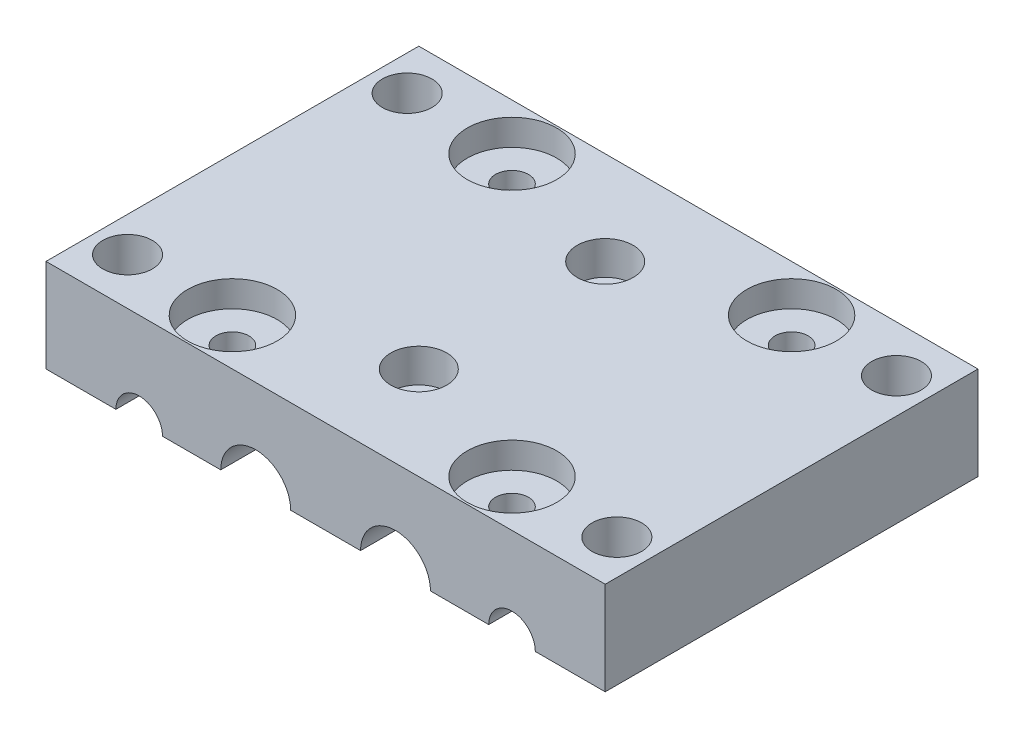
SolidWorks part; units mm, degrees
material "Copper"
ref_plane "Front Plane" through (0, 0, 0) normal (0, 0, 1) x (1, 0, 0)
ref_plane "Top Plane" through (0, 0, 0) normal (0, 1, 0) x (1, 0, 0)
ref_plane "Right Plane" through (0, 0, 0) normal (1, 0, 0) x (0, 0, -1)
sketch "Sketch1" plane through (0, 0, 0) normal (0, 1, 0) x (1, 0, 0)
  line L1 (-38.1, 25.4) -> (38.1, 25.4)
  line L2 (-38.1, 25.4) -> (-38.1, -25.4)
  line L3 (-38.1, -25.4) -> (38.1, -25.4)
  line L4 (38.1, 25.4) -> (38.1, -25.4)
  dimension "D1" = 50.8
  dimension "D2" = 76.2
  dimension "D3" = 38.1
  dimension "D4" = 25.4
extrude "Boss-Extrude1" add sketch "Sketch1" along normal blind 12.7
sketch "Sketch2" plane through (0, 0, 25.4) normal (0, 0, 1) x (1, 0, 0)
  line L0 (-38.1, 0) -> (38.1, 0) construction
  line L1 (-38.1, 12.7) -> (-38.1, 0) construction
  circle A0 centre (-25.4, 0) radius 3.175
  circle A1 centre (25.4, 0) radius 3.175
  dimension "D3" = 6.35
  dimension "D1" = 50.8
  dimension "D2" = 12.7
extrude "Cut-Extrude1" cut sketch "Sketch2" against normal through all
sketch "Sketch3" plane through (0, 0, 25.4) normal (0, 0, 1) x (1, 0, 0)
  line L0 (-22.225, 0) -> (22.225, 0) construction
  circle A0 centre (-9.525, 0) radius 4.7625
  circle A1 centre (9.525, 0) radius 4.7625
  dimension "D1" = 9.525
  dimension "D2" = 19.05
  dimension "D3" = 9.525
extrude "Cut-Extrude2" cut sketch "Sketch3" against normal through all
hole_wizard "1/4 Clearance Hole1" positions "Sketch5" profile "Sketch4" hole size "1/4" standard "ANSI Inch" end condition through all
sketch "Sketch5" plane through (0, 12.7, 0) normal (0, 1, 0) x (1, 0, 0)
  line L0 (-38.1, 25.4) -> (-38.1, -25.4) construction
  line L1 (38.1, 25.4) -> (-38.1, 25.4) construction
  line L2 (-38.1, -25.4) -> (-28.575, -25.4) construction
  line L3 (38.1, -25.4) -> (38.1, 25.4) construction
  point P0 (-33.3375, -19.05)
  point P2 (-33.3375, 19.05)
  point P4 (33.3375, 19.05)
  point P6 (33.3375, -19.05)
  point P17 (-33.3375, -25.4)
  dimension "D1" = 4.7625
  dimension "D2" = 6.35
  dimension "D3" = 6.35
  dimension "D4" = 4.7625
sketch "Sketch4" plane through (-33.3375, 12.7, 19.05) normal (1, 0, 0) x (0, 0, 1)
  line L0 (0, 0) -> (0, 12.7)
  line L1 (0, 12.7) -> (3.3782, 12.7)
  line L2 (3.3782, 12.7) -> (3.3782, 0)
  line L5 (3.3782, 0) -> (0, 0)
  line L11 (0, -6.35) -> (0, 107.95) construction
  dimension "Thru Hole Dia." = 6.7564
  dimension "Thru Hole Depth" = 12.7
hole_wizard "#8 Clearance Hole1" positions "Sketch7" profile "Sketch6" hole size "#8" standard "ANSI Inch" end condition through all
sketch "Sketch7" plane through (0, 12.7, 0) normal (0, 1, 0) x (1, 0, 0)
  point P0 (-19.05, 19.05)
  point P2 (-19.05, -19.05)
  point P4 (19.05, -19.05)
  point P6 (19.05, 19.05)
  point P14 (0, 12.7)
  point P16 (0, -12.7)
  dimension "D1" = 19.05
  dimension "D2" = 19.05
  dimension "D3" = 38.1
  dimension "D4" = 19.05
  dimension "D5" = 12.7
  dimension "D6" = 12.7
sketch "Sketch6" plane through (-19.05, 12.7, -19.05) normal (1, 0, 0) x (0, 0, 1)
  line L0 (0, 0) -> (0, 12.7)
  line L1 (0, 12.7) -> (2.2479, 12.7)
  line L2 (2.2479, 12.7) -> (2.2479, 0)
  line L5 (2.2479, 0) -> (0, 0)
  line L11 (0, -6.35) -> (0, 107.95) construction
  dimension "Thru Hole Dia." = 4.4958
  dimension "Thru Hole Depth" = 12.7
sketch "Sketch10" plane through (0, 12.7, 0) normal (0, 1, 0) x (1, 0, 0)
  circle A0 centre (0, 12.7) radius 3.81
  circle A1 centre (0, -12.7) radius 3.81
  dimension "D1" = 7.62
extrude "Cut-Extrude3" cut sketch "Sketch10" against normal blind 4.572
sketch "Sketch11" plane through (0, 12.7, 0) normal (0, 1, 0) x (1, 0, 0)
  circle A0 centre (-19.05, 19.05) radius 6.096
  circle A1 centre (-19.05, -19.05) radius 6.096
  circle A2 centre (19.05, -19.05) radius 6.096
  circle A3 centre (19.05, 19.05) radius 6.096
  dimension "D1" = 12.192
extrude "Cut-Extrude4" cut sketch "Sketch11" against normal blind 3.556
